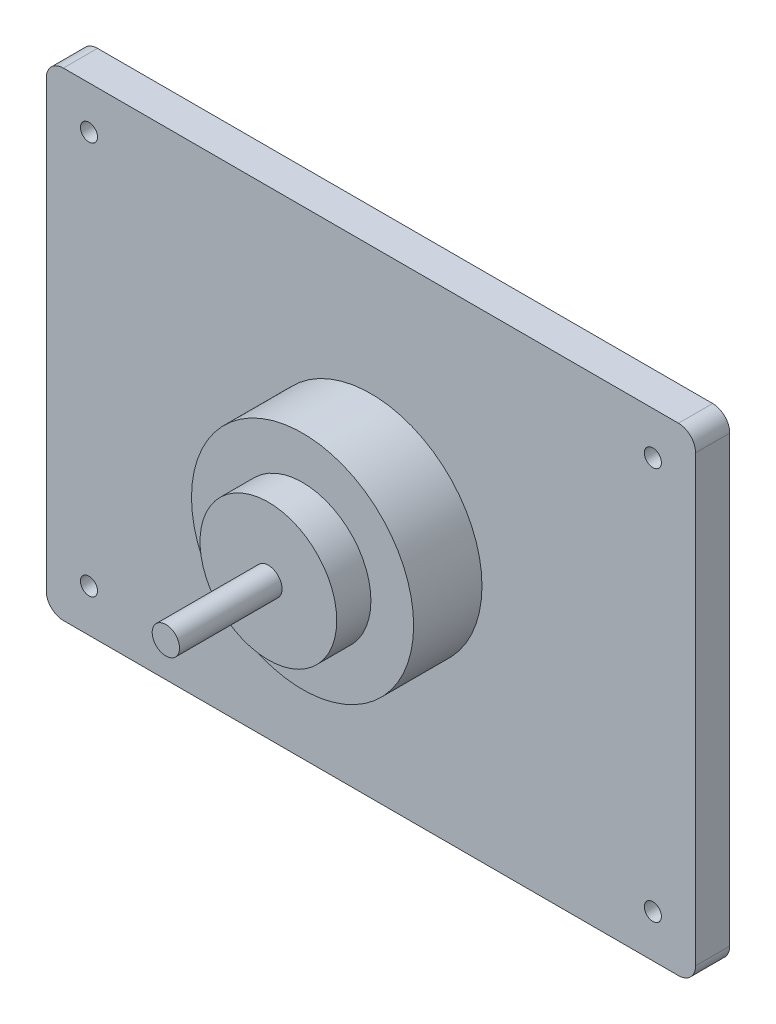
SolidWorks part; units mm, degrees
ref_plane "前视基准面" through (0, 0, 0) normal (0, 0, 1) x (1, 0, 0)
ref_plane "上视基准面" through (0, 0, 0) normal (0, 1, 0) x (1, 0, 0)
ref_plane "右视基准面" through (0, 0, 0) normal (1, 0, 0) x (0, 0, -1)
sketch "草图1" plane through (0, 0, 0) normal (0, 0, 1) x (1, 0, 0)
  line L0 (0, 0) -> (0, 50000) construction
  line L1 (0, 0) -> (50000, 0) construction
  line L3 (-95, 70) -> (95, 70)
  line L4 (-95, 70) -> (-95, -70)
  line L5 (-95, -70) -> (95, -70)
  line L6 (95, 70) -> (95, -70)
extrude "凸台-拉伸1" add sketch "草图1" along normal blind 10 contours L4 L3 L6 L5
fillet "圆角1" radius 5 4 edges at (-95, 70, 5) (-95, -70, 5) (95, -70, 5) (95, 70, 5)
sketch "草图2" plane through (0, 0, 10) normal (0, 0, 1) x (1, 0, 0)
  line L0 (0, 0) -> (50000, 0) construction
  line L1 (0, 0) -> (0, 50000) construction
  circle A0 centre (0, 0) radius 32.5
extrude "凸台-拉伸2" add sketch "草图2" along normal blind 20
sketch "草图3" plane through (0, 0, 30) normal (0, 0, 1) x (1, 0, 0)
  circle A0 centre (0, 0) radius 20
extrude "凸台-拉伸3" add sketch "草图3" along normal blind 10
sketch "草图4" plane through (0, 0, 40) normal (0, 0, 1) x (1, 0, 0)
  circle A0 centre (0, 0) radius 10
extrude "凸台-拉伸4" add sketch "草图4" along normal blind 20
sketch "草图5" plane through (0, 0, 60) normal (0, 0, 1) x (1, 0, 0)
  circle A0 centre (0, 0) radius 4
  circle A1 centre (0, 0) radius 10
extrude "切除-拉伸1" cut sketch "草图5" against normal blind 10
sketch "草图6" plane through (0, 0, 50) normal (0, 0, 1) x (1, 0, 0)
  circle A0 centre (0, 0) radius 4
  circle A1 centre (0, 0) radius 10
extrude "切除-拉伸2" cut sketch "草图6" against normal blind 10
sketch "草图7" plane through (0, 0, 60) normal (0, 0, 1) x (1, 0, 0)
  circle A0 centre (0, 0) radius 4
extrude "凸台-拉伸5" add sketch "草图7" along normal blind 10
sketch "草图8" plane through (0, 0, 10) normal (0, 0, 1) x (1, 0, 0)
  line L0 (-90, 70) -> (90, 70) construction
  line L1 (95, 65) -> (95, -65) construction
  line L2 (-133.379, 0) -> (133.379, 0) construction
  line L3 (0, 0) -> (0, 50000) construction
  circle A0 centre (82.5, 57.5) radius 2.5
  circle A1 centre (82.5, -57.5) radius 2.5
  circle A2 centre (-82.5, -57.5) radius 2.5
  circle A3 centre (-82.5, 57.5) radius 2.5
  point P12 (0, 0)
  dimension "D1" = 12.5
  dimension "D2" = 12.5
extrude "切除-拉伸3" cut sketch "草图8" against normal blind 10
